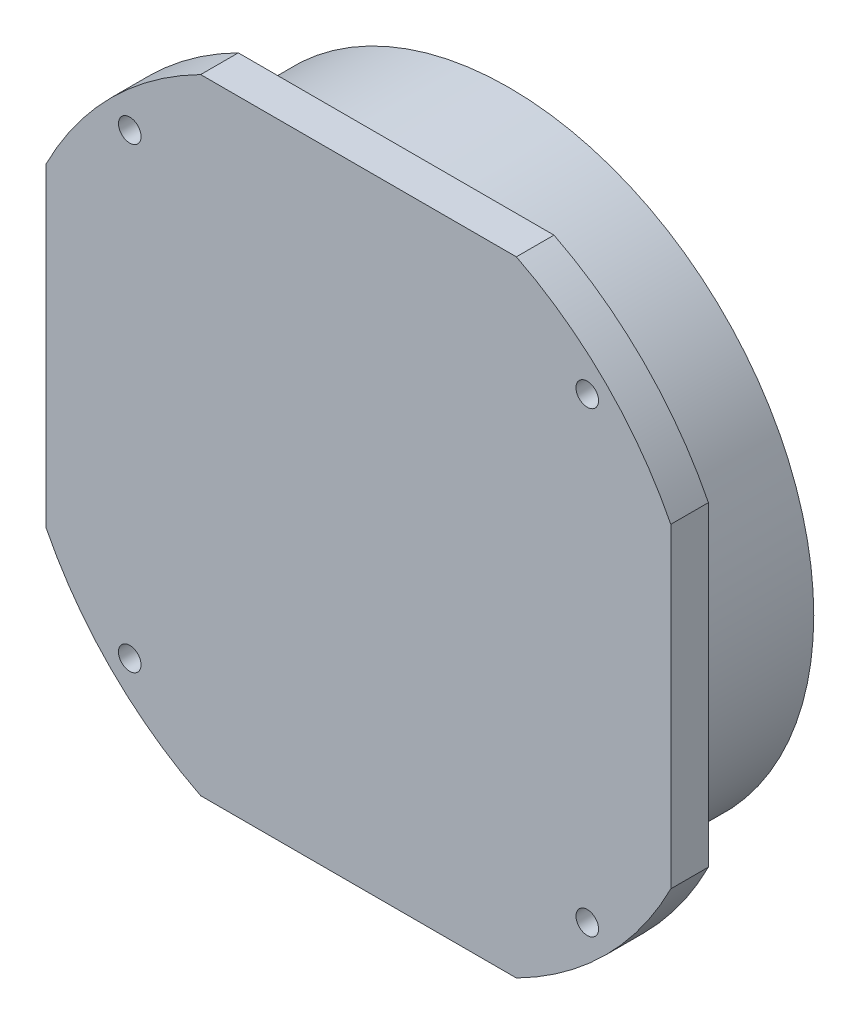
SolidWorks part; units mm, degrees
ref_plane "前视基准面" through (0, 0, 0) normal (0, 0, 1) x (1, 0, 0)
ref_plane "上视基准面" through (0, 0, 0) normal (0, 1, 0) x (1, 0, 0)
ref_plane "右视基准面" through (0, 0, 0) normal (1, 0, 0) x (0, 0, -1)
sketch "草图1" plane through (0, 0, 0) normal (0, 0, 1) x (1, 0, 0)
  line L1 (-20.9762, 41.5) -> (20.9762, 41.5)
  line L2 (-41.5, 20.9762) -> (-41.5, -20.9762)
  line L3 (-20.9762, -41.5) -> (20.9762, -41.5)
  line L4 (41.5, 20.9762) -> (41.5, -20.9762)
  line L5 (-41.5, 41.5) -> (41.5, -41.5) construction
  line L6 (-41.5, -41.5) -> (41.5, 41.5) construction
  arc A0 (-41.5, -20.9762) -> (-20.9762, -41.5) centre (0, 0) ccw
  arc A1 (-20.9762, 41.5) -> (-41.5, 20.9762) centre (0, 0) ccw
  arc A2 (41.5, 20.9762) -> (20.9762, 41.5) centre (0, 0) ccw
  arc A3 (20.9762, -41.5) -> (41.5, -20.9762) centre (0, 0) ccw
  dimension "D1" = 93
  dimension "D2" = 83
extrude "凸台-拉伸1" add sketch "草图1" along normal blind 5
sketch "草图2" plane through (0, 0, 5) normal (0, 0, 1) x (1, 0, 0)
  line L1 (-30.4, 30.4) -> (30.4, 30.4) construction
  line L2 (-30.4, 30.4) -> (-30.4, -30.4) construction
  line L3 (-30.4, -30.4) -> (30.4, -30.4) construction
  line L4 (30.4, 30.4) -> (30.4, -30.4) construction
  line L5 (-30.4, 30.4) -> (30.4, -30.4) construction
  line L6 (-30.4, -30.4) -> (30.4, 30.4) construction
  circle A0 centre (-30.4, 30.4) radius 1.5
  circle A1 centre (30.4, 30.4) radius 1.5
  circle A2 centre (30.4, -30.4) radius 1.5
  circle A3 centre (-30.4, -30.4) radius 1.5
  point P0 (0, 0)
  dimension "D1" = 60.8
  dimension "D2" = 3
  dimension "D3" = 3
  dimension "D4" = 3
  dimension "D5" = 3
extrude "切除-拉伸1" cut sketch "草图2" against normal blind 19
cosmetic thread "装饰螺纹线1" parameters "D2"=3.2
cosmetic thread "装饰螺纹线2" parameters "D2"=3.2
cosmetic thread "装饰螺纹线3" parameters "D2"=3.2
cosmetic thread "装饰螺纹线4" parameters "D2"=3.2
sketch "草图3" plane through (0, 0, 0) normal (0, 0, -1) x (-1, 0, 0)
  circle A0 centre (0, 0) radius 40.5
  dimension "D1" = 81
extrude "凸台-拉伸2" add sketch "草图3" along normal blind 15
sketch "草图6" plane through (0, 0, -15) normal (0, 0, -1) x (-1, 0, 0)
  line L0 (-52.0695, 0) -> (48.2987, 0) construction
  line L1 (0, 52.3499) -> (0, -54.6701) construction
  line L2 (-52.0695, -9.5) -> (48.2987, -9.5) construction
  line L3 (-18, -5.75) -> (-18, -7.75)
  line L4 (-20, -56.9139) -> (-20, 52.3499) construction
  line L5 (-21.5, -8.25) -> (-18.5, -8.25)
  line L6 (-22, -8.75) -> (-22, -10.75)
  line L7 (-22, -10.75) -> (-18, -10.75)
  line L8 (-18, -8.75) -> (-18, -10.75)
  line L9 (-22, -8.25) -> (-18, -10.75) construction
  line L10 (-22, -10.75) -> (-18, -8.25) construction
  line L11 (-22, -7.75) -> (-18, -5.25) construction
  line L12 (-21.5, -5.25) -> (-18.5, -5.25)
  line L13 (-22, -5.75) -> (-22, -7.75)
  line L14 (-22, -7.75) -> (-18, -7.75)
  line L15 (-22, -5.25) -> (-18, -7.75) construction
  line L16 (-18, -2.75) -> (-18, -4.75)
  line L17 (-22, -2.75) -> (-22, -4.75)
  line L18 (-21.5, -2.25) -> (-18.5, -2.25)
  line L19 (-22, -2.25) -> (-18, -4.75) construction
  line L20 (-22, -4.75) -> (-18, -2.25) construction
  line L21 (-22, -4.75) -> (-18, -4.75)
  line L22 (-21.5, -11.25) -> (-18.5, -11.25)
  line L23 (-22, -14.75) -> (-22, -16.75)
  line L24 (-18, -14.75) -> (-18, -16.75)
  line L25 (-18, -11.75) -> (-18, -13.75)
  line L26 (-22, -13.75) -> (-18, -13.75)
  line L27 (-22, -16.75) -> (-18, -14.25) construction
  line L28 (-22, -11.75) -> (-22, -13.75)
  line L29 (-22, -16.75) -> (-18, -16.75)
  line L30 (-21.5, -14.25) -> (-18.5, -14.25)
  line L31 (-22, -11.25) -> (-18, -13.75) construction
  line L32 (-22, -13.75) -> (-18, -11.25) construction
  line L33 (-22, -14.25) -> (-18, -16.75) construction
  arc A0 (-18.5, -8.25) -> (-18, -8.75) centre (-18.5, -8.75) cw
  arc A1 (-21.5, -8.25) -> (-22, -8.75) centre (-21.5, -8.75) ccw
  arc A2 (-18.5, -5.25) -> (-18, -5.75) centre (-18.5, -5.75) cw
  arc A3 (-21.5, -5.25) -> (-22, -5.75) centre (-21.5, -5.75) ccw
  arc A4 (-18.5, -2.25) -> (-18, -2.75) centre (-18.5, -2.75) cw
  arc A5 (-21.5, -2.25) -> (-22, -2.75) centre (-21.5, -2.75) ccw
  arc A6 (-21.5, -11.25) -> (-22, -11.75) centre (-21.5, -11.75) ccw
  arc A7 (-21.5, -14.25) -> (-22, -14.75) centre (-21.5, -14.75) ccw
  arc A8 (-18.5, -11.25) -> (-18, -11.75) centre (-18.5, -11.75) cw
  arc A9 (-18.5, -14.25) -> (-18, -14.75) centre (-18.5, -14.75) cw
  point P7 (-20, -9.5)
  point P20 (-20, -6.4301)
  point P41 (-20, -15.4923)
  dimension "D5" = 0.5
  dimension "D1" = 9.5
  dimension "D2" = 20
  dimension "D3" = 2.5
  dimension "D4" = 4
  dimension "D6" = 0.5
  dimension "D7" = 0.5
  dimension "D8" = 0.5
  dimension "D9" = 0.5
extrude "凸台-拉伸3" add sketch "草图6" along normal blind 1
sketch "草图7" plane through (0, 0, -16) normal (0, 0, -1) x (-1, 0, 0)
  line L0 (-19.0484, -6.34) -> (-19.0484, -6.74)
  line L1 (-21.0314, -3.1888) -> (-20.8314, -3.1888)
  line L2 (-21.0314, -3.1888) -> (-21.0314, -3.9888)
  line L3 (-21.0314, -3.9888) -> (-20.8314, -3.9888)
  line L4 (-20.8314, -3.1888) -> (-20.8314, -3.9888)
  line L5 (-21.0314, -3.1888) -> (-20.8314, -3.9888) construction
  line L6 (-21.0314, -3.9888) -> (-20.8314, -3.1888) construction
  line L7 (-19.4484, -3.3888) -> (-19.0484, -3.3888)
  line L8 (-19.4484, -3.3888) -> (-19.4484, -3.7888)
  line L9 (-19.4484, -3.7888) -> (-19.0484, -3.7888)
  line L10 (-19.0484, -3.3888) -> (-19.0484, -3.7888)
  line L11 (-19.4484, -3.3888) -> (-19.0484, -3.7888) construction
  line L12 (-19.4484, -3.7888) -> (-19.0484, -3.3888) construction
  line L13 (-21.0314, -6.94) -> (-20.8314, -6.14) construction
  line L14 (-19.4484, -6.34) -> (-19.4484, -6.74)
  line L15 (-21.0314, -6.14) -> (-20.8314, -6.14)
  line L16 (-21.0314, -6.94) -> (-20.8314, -6.94)
  line L17 (-19.4484, -6.74) -> (-19.0484, -6.34) construction
  line L18 (-19.4484, -6.34) -> (-19.0484, -6.34)
  line L19 (-21.0314, -6.14) -> (-20.8314, -6.94) construction
  line L20 (-21.0314, -6.14) -> (-21.0314, -6.94)
  line L21 (-20.8314, -6.14) -> (-20.8314, -6.94)
  line L22 (-19.4484, -6.34) -> (-19.0484, -6.74) construction
  line L23 (-19.4484, -6.74) -> (-19.0484, -6.74)
  line L24 (-19.4484, -9.397) -> (-19.0484, -9.797) construction
  line L25 (-19.4484, -9.397) -> (-19.0484, -9.397)
  line L26 (-21.0314, -9.997) -> (-20.8314, -9.997)
  line L27 (-19.4484, -9.797) -> (-19.0484, -9.397) construction
  line L28 (-19.4484, -9.797) -> (-19.0484, -9.797)
  line L29 (-21.0314, -9.197) -> (-20.8314, -9.997) construction
  line L30 (-21.0314, -9.197) -> (-20.8314, -9.197)
  line L31 (-20.8314, -9.197) -> (-20.8314, -9.997)
  line L32 (-19.0484, -9.397) -> (-19.0484, -9.797)
  line L33 (-21.0314, -9.197) -> (-21.0314, -9.997)
  line L34 (-19.4484, -9.397) -> (-19.4484, -9.797)
  line L35 (-21.0314, -9.997) -> (-20.8314, -9.197) construction
  line L36 (-21.0314, -12.9162) -> (-20.8314, -12.1162) construction
  line L37 (-19.4484, -12.7162) -> (-19.0484, -12.3162) construction
  line L38 (-21.0314, -12.1162) -> (-21.0314, -12.9162)
  line L39 (-19.4484, -12.7162) -> (-19.0484, -12.7162)
  line L40 (-19.4484, -12.3162) -> (-19.4484, -12.7162)
  line L41 (-21.0314, -12.9162) -> (-20.8314, -12.9162)
  line L42 (-20.8314, -12.1162) -> (-20.8314, -12.9162)
  line L43 (-19.4484, -12.3162) -> (-19.0484, -12.3162)
  line L44 (-21.0314, -12.1162) -> (-20.8314, -12.1162)
  line L45 (-21.0314, -12.1162) -> (-20.8314, -12.9162) construction
  line L46 (-19.4484, -12.3162) -> (-19.0484, -12.7162) construction
  line L47 (-19.0484, -12.3162) -> (-19.0484, -12.7162)
  line L48 (-19.0484, -15.2449) -> (-19.0484, -15.6449)
  line L49 (-21.0314, -15.8449) -> (-20.8314, -15.0449) construction
  line L50 (-19.4484, -15.2449) -> (-19.4484, -15.6449)
  line L51 (-19.4484, -15.2449) -> (-19.0484, -15.6449) construction
  line L52 (-21.0314, -15.0449) -> (-20.8314, -15.8449) construction
  line L53 (-20.8314, -15.0449) -> (-20.8314, -15.8449)
  line L54 (-19.4484, -15.6449) -> (-19.0484, -15.6449)
  line L55 (-19.4484, -15.2449) -> (-19.0484, -15.2449)
  line L56 (-21.0314, -15.8449) -> (-20.8314, -15.8449)
  line L57 (-21.0314, -15.0449) -> (-21.0314, -15.8449)
  line L58 (-19.4484, -15.6449) -> (-19.0484, -15.2449) construction
  line L59 (-21.0314, -15.0449) -> (-20.8314, -15.0449)
  point P0 (-20.9314, -3.5888)
  point P5 (-19.2484, -3.5888)
  point P10 (-20.9314, -6.54)
  point P15 (-19.2484, -6.54)
  point P20 (-20.9314, -9.597)
  point P25 (-19.2484, -9.597)
  point P30 (-20.9314, -12.5162)
  point P35 (-19.2484, -12.5162)
  point P40 (-20.9314, -15.4449)
  point P45 (-19.2484, -15.4449)
  dimension "D1" = 0.8
  dimension "D2" = 0.2
  dimension "D3" = 0.4
extrude "凸台-拉伸4" add sketch "草图7" along normal blind 7
sketch "草图8" plane through (0, 0, -15) normal (0, 0, -1) x (-1, 0, 0)
  line L0 (-60.7271, 0) -> (56.5673, 0) construction
  line L1 (0, 56.1347) -> (0, -56.818) construction
  line L2 (-20, 59.9555) -> (-20, -62.788) construction
  line L3 (-60.7271, -9.5) -> (56.5673, -9.5) construction
  circle A0 centre (-20, 0) radius 1.5
  circle A1 centre (-20, 0) radius 1.65
  circle A2 centre (-20, -19) radius 1.5
  circle A3 centre (-20, -19) radius 1.65
  dimension "D3" = 3
  dimension "D4" = 3.3
  dimension "D5" = 3
  dimension "D6" = 9.5
  dimension "D7" = 3.3
  dimension "D1" = 20
  dimension "D2" = 9.5
extrude "切除-拉伸2" cut sketch "草图8" against normal blind 0.5
sketch "草图9" plane through (0, 0, -15) normal (0, 0, -1) x (-1, 0, 0)
  line L0 (-21.3007, 0.7471) -> (-19.0962, -1.1971)
  line L1 (-20.9038, 1.1971) -> (-18.6993, -0.7471)
  line L2 (-21.3007, -18.2529) -> (-19.0962, -20.1971)
  line L3 (-20.9038, -17.8029) -> (-18.6993, -19.7471)
  circle A0 centre (-20, 0) radius 1.5 construction
  arc A1 (-19.0962, -1.1971) -> (-18.6993, -0.7471) centre (-20, 0) ccw
  arc A2 (-20.9038, 1.1971) -> (-21.3007, 0.7471) centre (-20, 0) ccw
  arc A3 (-20.9038, -17.8029) -> (-21.3007, -18.2529) centre (-20, -19) ccw
  arc A4 (-19.0962, -20.1971) -> (-18.6993, -19.7471) centre (-20, -19) ccw
  dimension "D1" = 0.3
  dimension "D2" = 0.6
  dimension "D3" = 0.3
  dimension "D4" = 0.6
extrude "切除-拉伸3" cut sketch "草图9" against normal blind 0.5
